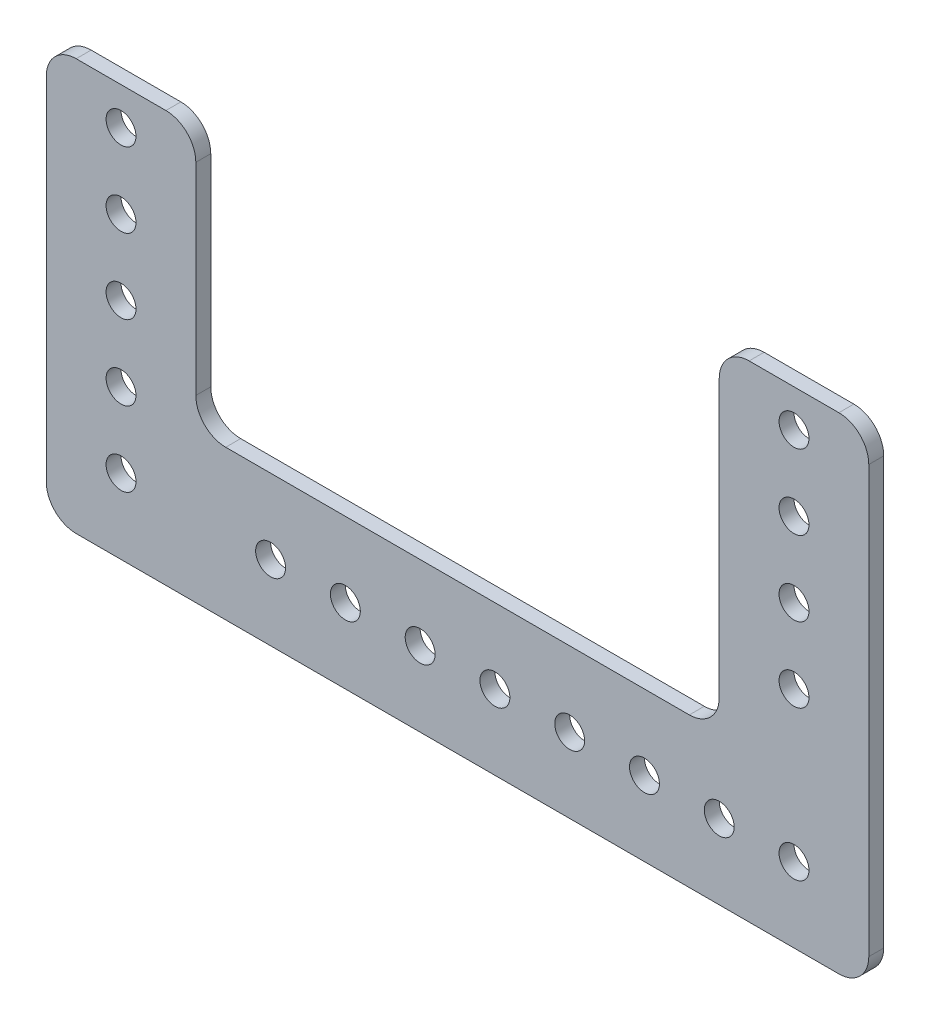
SolidWorks part; units mm, degrees
ref_plane "Front Plane" through (0, 0, 0) normal (0, 0, 1) x (1, 0, 0)
ref_plane "Top Plane" through (0, 0, 0) normal (0, 1, 0) x (1, 0, 0)
ref_plane "Right Plane" through (0, 0, 0) normal (1, 0, 0) x (0, 0, -1)
sketch "Sketch1" plane through (0, 0, 0) normal (0, 0, 1) x (1, 0, 0)
  line L0 (330.2, 285.75) -> (330.2, 273.05) construction
  line L1 (317.5, 298.45) -> (342.9, 298.45)
  line L2 (317.5, 298.45) -> (317.5, 57.15)
  line L3 (317.5, 57.15) -> (342.9, 57.15)
  line L4 (342.9, 298.45) -> (342.9, 57.15)
  line L5 (342.9, 298.45) -> (838.2, 298.45)
  line L6 (342.9, 298.45) -> (342.9, 273.05)
  line L7 (342.9, 273.05) -> (838.2, 273.05)
  line L8 (838.2, 298.45) -> (838.2, 273.05)
  line L9 (342.9, 82.55) -> (838.2, 82.55)
  line L10 (342.9, 82.55) -> (342.9, 57.15)
  line L11 (342.9, 57.15) -> (838.2, 57.15)
  line L12 (838.2, 82.55) -> (838.2, 57.15)
  line L13 (431.8, 273.05) -> (457.2, 273.05)
  line L14 (431.8, 273.05) -> (431.8, 82.55)
  line L15 (431.8, 82.55) -> (457.2, 82.55)
  line L16 (457.2, 273.05) -> (457.2, 82.55)
  line L17 (444.5, 260.35) -> (444.5, 247.65) construction
  line L18 (355.6, 285.75) -> (368.3, 285.75) construction
  circle A0 centre (330.2, 285.75) radius 2.54
  circle A1 centre (330.2, 273.05) radius 2.54
  circle A2 centre (330.2, 260.35) radius 2.54
  circle A3 centre (330.2, 247.65) radius 2.54
  circle A4 centre (330.2, 234.95) radius 2.54
  circle A5 centre (330.2, 222.25) radius 2.54
  circle A6 centre (330.2, 209.55) radius 2.54
  circle A7 centre (330.2, 196.85) radius 2.54
  circle A8 centre (330.2, 184.15) radius 2.54
  circle A9 centre (330.2, 171.45) radius 2.54
  circle A10 centre (330.2, 158.75) radius 2.54
  circle A11 centre (330.2, 146.05) radius 2.54
  circle A12 centre (330.2, 133.35) radius 2.54
  circle A13 centre (330.2, 120.65) radius 2.54
  circle A14 centre (330.2, 107.95) radius 2.54
  circle A15 centre (330.2, 95.25) radius 2.54
  circle A16 centre (330.2, 82.55) radius 2.54
  circle A17 centre (330.2, 69.85) radius 2.54
  circle A18 centre (444.5, 260.35) radius 2.54
  circle A19 centre (444.5, 247.65) radius 2.54
  circle A20 centre (444.5, 234.95) radius 2.54
  circle A21 centre (444.5, 222.25) radius 2.54
  circle A22 centre (444.5, 209.55) radius 2.54
  circle A23 centre (444.5, 196.85) radius 2.54
  circle A24 centre (444.5, 184.15) radius 2.54
  circle A25 centre (444.5, 171.45) radius 2.54
  circle A26 centre (444.5, 158.75) radius 2.54
  circle A27 centre (444.5, 146.05) radius 2.54
  circle A28 centre (444.5, 133.35) radius 2.54
  circle A29 centre (444.5, 120.65) radius 2.54
  circle A30 centre (444.5, 107.95) radius 2.54
  circle A31 centre (444.5, 95.25) radius 2.54
  circle A32 centre (355.6, 69.85) radius 2.54
  circle A33 centre (355.6, 285.75) radius 2.54
  circle A34 centre (368.3, 285.75) radius 2.54
  circle A35 centre (368.3, 69.85) radius 2.54
  circle A36 centre (381, 285.75) radius 2.54
  circle A37 centre (381, 69.85) radius 2.54
  circle A38 centre (393.7, 285.75) radius 2.54
  circle A39 centre (393.7, 69.85) radius 2.54
  circle A40 centre (406.4, 285.75) radius 2.54
  circle A41 centre (406.4, 69.85) radius 2.54
  circle A42 centre (419.1, 285.75) radius 2.54
  circle A43 centre (419.1, 69.85) radius 2.54
  circle A44 centre (431.8, 285.75) radius 2.54
  circle A45 centre (431.8, 69.85) radius 2.54
  circle A46 centre (444.5, 285.75) radius 2.54
  circle A47 centre (444.5, 69.85) radius 2.54
  circle A48 centre (457.2, 285.75) radius 2.54
  circle A49 centre (457.2, 69.85) radius 2.54
  circle A50 centre (469.9, 285.75) radius 2.54
  circle A51 centre (469.9, 69.85) radius 2.54
  circle A52 centre (482.6, 285.75) radius 2.54
  circle A53 centre (482.6, 69.85) radius 2.54
  circle A54 centre (495.3, 285.75) radius 2.54
  circle A55 centre (495.3, 69.85) radius 2.54
  circle A56 centre (508, 285.75) radius 2.54
  circle A57 centre (508, 69.85) radius 2.54
  circle A58 centre (520.7, 285.75) radius 2.54
  circle A59 centre (520.7, 69.85) radius 2.54
  circle A60 centre (533.4, 285.75) radius 2.54
  circle A61 centre (533.4, 69.85) radius 2.54
  circle A62 centre (546.1, 285.75) radius 2.54
  circle A63 centre (546.1, 69.85) radius 2.54
  circle A64 centre (558.8, 285.75) radius 2.54
  circle A65 centre (558.8, 69.85) radius 2.54
  circle A66 centre (571.5, 285.75) radius 2.54
  circle A67 centre (571.5, 69.85) radius 2.54
  circle A68 centre (584.2, 285.75) radius 2.54
  circle A69 centre (584.2, 69.85) radius 2.54
  circle A70 centre (596.9, 285.75) radius 2.54
  circle A71 centre (596.9, 69.85) radius 2.54
  circle A72 centre (609.6, 285.75) radius 2.54
  circle A73 centre (609.6, 69.85) radius 2.54
  circle A74 centre (622.3, 285.75) radius 2.54
  circle A75 centre (622.3, 69.85) radius 2.54
  circle A76 centre (635, 285.75) radius 2.54
  circle A77 centre (635, 69.85) radius 2.54
  circle A78 centre (647.7, 285.75) radius 2.54
  circle A79 centre (647.7, 69.85) radius 2.54
  circle A80 centre (660.4, 285.75) radius 2.54
  circle A81 centre (660.4, 69.85) radius 2.54
  circle A82 centre (673.1, 285.75) radius 2.54
  circle A83 centre (673.1, 69.85) radius 2.54
  circle A84 centre (685.8, 285.75) radius 2.54
  circle A85 centre (685.8, 69.85) radius 2.54
  circle A86 centre (698.5, 285.75) radius 2.54
  circle A87 centre (698.5, 69.85) radius 2.54
  circle A88 centre (711.2, 285.75) radius 2.54
  circle A89 centre (711.2, 69.85) radius 2.54
  circle A90 centre (723.9, 285.75) radius 2.54
  circle A91 centre (723.9, 69.85) radius 2.54
  circle A92 centre (736.6, 285.75) radius 2.54
  circle A93 centre (736.6, 69.85) radius 2.54
  circle A94 centre (749.3, 285.75) radius 2.54
  circle A95 centre (749.3, 69.85) radius 2.54
  circle A96 centre (762, 285.75) radius 2.54
  circle A97 centre (762, 69.85) radius 2.54
  circle A98 centre (774.7, 285.75) radius 2.54
  circle A99 centre (774.7, 69.85) radius 2.54
  circle A100 centre (787.4, 285.75) radius 2.54
  circle A101 centre (787.4, 69.85) radius 2.54
  circle A102 centre (800.1, 285.75) radius 2.54
  circle A103 centre (800.1, 69.85) radius 2.54
  circle A104 centre (812.8, 285.75) radius 2.54
  circle A105 centre (812.8, 69.85) radius 2.54
  circle A106 centre (825.5, 285.75) radius 2.54
  circle A107 centre (825.5, 69.85) radius 2.54
  dimension "D3" = 5.08
  dimension "D8" = 5.08
  dimension "D13" = 5.08
  dimension "D14" = 5.08
  dimension "D1" = 12.7
  dimension "D2" = 12.7
  dimension "D5" = 12.7
  dimension "D6" = 12.7
  dimension "D7" = 12.7
  dimension "D10" = 12.7
  dimension "D11" = 12.7
  dimension "D12" = 12.7
  dimension "D15" = 12.7
  dimension "D4" = 18
  dimension "D9" = 14
  dimension "D16" = 38
sketch "Sketch2" plane through (0, 0, 0) normal (0, 0, 1) x (1, 0, 0)
  line L0 (317.5, 62.23) -> (317.5, 121.92)
  line L1 (317.5, 298.45) -> (317.5, 57.15) construction
  line L2 (322.58, 127) -> (337.82, 127)
  line L3 (342.9, 298.45) -> (342.9, 57.15) construction
  line L4 (342.9, 121.92) -> (342.9, 87.63)
  line L5 (347.98, 82.55) -> (426.72, 82.55)
  line L6 (431.8, 87.63) -> (431.8, 134.62)
  line L7 (431.8, 273.05) -> (431.8, 82.55) construction
  line L8 (436.88, 139.7) -> (452.12, 139.7)
  line L9 (457.2, 273.05) -> (457.2, 82.55) construction
  line L10 (457.2, 134.62) -> (457.2, 82.55)
  line L11 (457.2, 82.55) -> (457.2, 62.23)
  line L12 (342.9, 57.15) -> (838.2, 57.15) construction
  line L13 (452.12, 57.15) -> (322.58, 57.15)
  circle A0 centre (444.5, 133.35) radius 2.54 construction
  circle A1 centre (444.5, 120.65) radius 2.54 construction
  circle A2 centre (444.5, 107.95) radius 2.54 construction
  circle A3 centre (444.5, 95.25) radius 2.54 construction
  circle A4 centre (444.5, 69.85) radius 2.54 construction
  circle A5 centre (431.8, 69.85) radius 2.54 construction
  circle A6 centre (419.1, 69.85) radius 2.54 construction
  circle A7 centre (406.4, 69.85) radius 2.54 construction
  circle A8 centre (393.7, 69.85) radius 2.54 construction
  circle A9 centre (381, 69.85) radius 2.54 construction
  circle A10 centre (368.3, 69.85) radius 2.54 construction
  circle A11 centre (355.6, 69.85) radius 2.54 construction
  circle A12 centre (330.2, 69.85) radius 2.54 construction
  circle A13 centre (330.2, 82.55) radius 2.54 construction
  circle A14 centre (330.2, 95.25) radius 2.54 construction
  circle A15 centre (330.2, 107.95) radius 2.54 construction
  circle A16 centre (330.2, 120.65) radius 2.54 construction
  circle A17 centre (444.5, 133.35) radius 2.54
  circle A18 centre (444.5, 120.65) radius 2.54
  circle A19 centre (444.5, 107.95) radius 2.54
  circle A20 centre (444.5, 95.25) radius 2.54
  circle A21 centre (444.5, 69.85) radius 2.54
  circle A22 centre (431.8, 69.85) radius 2.54
  circle A23 centre (419.1, 69.85) radius 2.54
  circle A24 centre (406.4, 69.85) radius 2.54
  circle A25 centre (393.7, 69.85) radius 2.54
  circle A26 centre (381, 69.85) radius 2.54
  circle A27 centre (368.3, 69.85) radius 2.54
  circle A28 centre (355.6, 69.85) radius 2.54
  circle A29 centre (330.2, 69.85) radius 2.54
  circle A30 centre (330.2, 82.55) radius 2.54
  circle A31 centre (330.2, 95.25) radius 2.54
  circle A32 centre (330.2, 107.95) radius 2.54
  circle A33 centre (330.2, 120.65) radius 2.54
  arc A34 (457.2, 62.23) -> (452.12, 57.15) centre (452.12, 62.23) cw
  arc A35 (452.12, 139.7) -> (457.2, 134.62) centre (452.12, 134.62) cw
  arc A36 (431.8, 134.62) -> (436.88, 139.7) centre (436.88, 134.62) cw
  arc A37 (426.72, 82.55) -> (431.8, 87.63) centre (426.72, 87.63) ccw
  arc A38 (342.9, 87.63) -> (347.98, 82.55) centre (347.98, 87.63) ccw
  arc A39 (317.5, 62.23) -> (322.58, 57.15) centre (322.58, 62.23) ccw
  arc A40 (317.5, 121.92) -> (322.58, 127) centre (322.58, 121.92) cw
  arc A41 (337.82, 127) -> (342.9, 121.92) centre (337.82, 121.92) cw
  point P76 (457.2, 57.15)
  point P79 (457.2, 139.7)
  point P82 (431.8, 139.7)
  point P85 (431.8, 82.55)
  point P88 (342.9, 82.55)
  point P91 (317.5, 57.15)
  point P94 (317.5, 127)
  point P97 (342.9, 127)
  dimension "D3" = 5.08
  dimension "D1" = 69.85
  dimension "D2" = 82.55
extrude "Boss-Extrude1" add sketch "Sketch2" along normal blind 2.54
